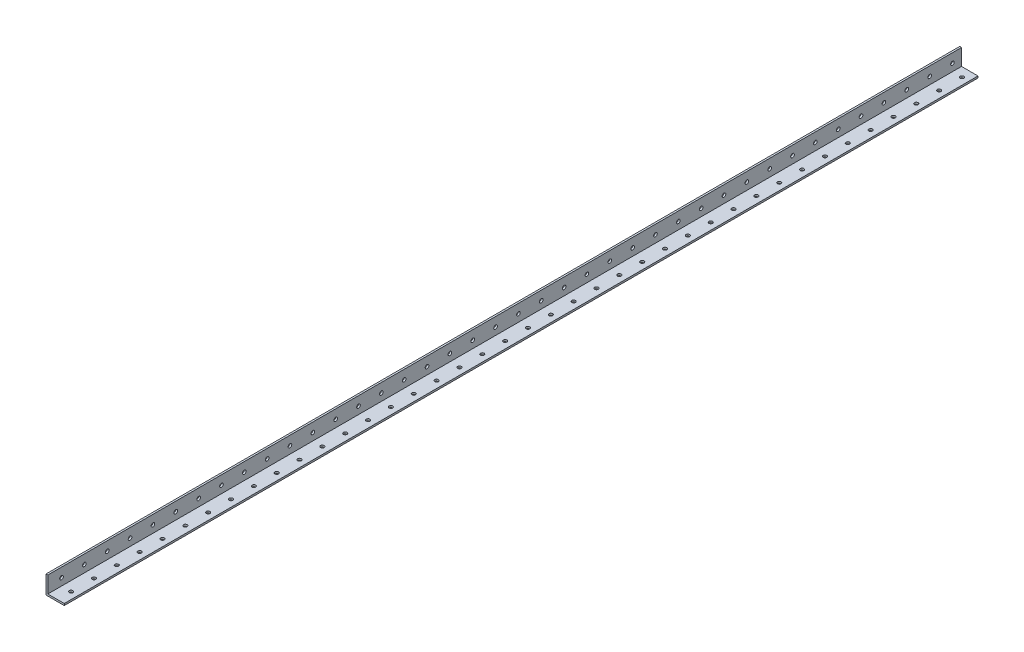
SolidWorks part; units mm, degrees
material "Aleación 6061"
ref_plane "Plan de face" through (0, 0, 0) normal (0, 0, 1) x (1, 0, 0)
ref_plane "Plan de dessus" through (0, 0, 0) normal (0, 1, 0) x (1, 0, 0)
ref_plane "Plan de droite" through (0, 0, 0) normal (1, 0, 0) x (0, 0, -1)
sketch "Croquis1" plane through (0, 0, 0) normal (0, 0, 1) x (1, 0, 0)
  line L0 (0, 0) -> (0, 40)
  line L1 (0, 40) -> (4, 40)
  line L2 (0, 0) -> (40, 0)
  line L3 (40, 0) -> (40, 4)
  line L4 (40, 4) -> (4, 4)
  line L5 (4, 4) -> (4, 40)
  dimension "D1" = 40
  dimension "D2" = 4
  dimension "D3" = 40
  dimension "D4" = 4
extrude "Saliente-Extruir1" add sketch "Croquis1" along normal blind 2000
sketch "Croquis2" plane through (0, 4, 0) normal (0, 1, 0) x (1, 0, 0)
  line L0 (40, -2000) -> (40, 0) construction
  line L1 (40, 0) -> (4, 0) construction
  circle A0 centre (25, -20) radius 4
  dimension "D1" = 8
  dimension "D2" = 15
  dimension "D3" = 20
extrude "Cortar-Extruir1" cut sketch "Croquis2" against normal blind 10
pattern_linear "MatrizL1" count 40 spacing 50 along (0, 0, 1) of "Cortar-Extruir1"
sketch "Sketch1" plane through (0, 0, 0) normal (-1, 0, 0) x (0, 0, 1)
  line L0 (2000, 40) -> (0, 40) construction
  line L2 (0, 40) -> (0, 0) construction
  circle A0 centre (20, 20) radius 4
  circle A1 centre (70, 20) radius 4
  circle A2 centre (120, 20) radius 4
  circle A3 centre (170, 20) radius 4
  circle A4 centre (220, 20) radius 4
  circle A5 centre (270, 20) radius 4
  circle A6 centre (320, 20) radius 4
  circle A7 centre (370, 20) radius 4
  circle A8 centre (420, 20) radius 4
  circle A9 centre (470, 20) radius 4
  circle A10 centre (520, 20) radius 4
  circle A11 centre (570, 20) radius 4
  circle A12 centre (620, 20) radius 4
  circle A13 centre (670, 20) radius 4
  circle A14 centre (720, 20) radius 4
  circle A15 centre (770, 20) radius 4
  circle A16 centre (820, 20) radius 4
  circle A17 centre (870, 20) radius 4
  circle A18 centre (920, 20) radius 4
  circle A19 centre (970, 20) radius 4
  circle A20 centre (1020, 20) radius 4
  circle A21 centre (1070, 20) radius 4
  circle A22 centre (1120, 20) radius 4
  circle A23 centre (1170, 20) radius 4
  circle A24 centre (1220, 20) radius 4
  circle A25 centre (1270, 20) radius 4
  circle A26 centre (1320, 20) radius 4
  circle A27 centre (1370, 20) radius 4
  circle A28 centre (1420, 20) radius 4
  circle A29 centre (1470, 20) radius 4
  circle A30 centre (1520, 20) radius 4
  circle A31 centre (1570, 20) radius 4
  circle A32 centre (1620, 20) radius 4
  circle A33 centre (1670, 20) radius 4
  circle A34 centre (1720, 20) radius 4
  circle A35 centre (1770, 20) radius 4
  circle A36 centre (1820, 20) radius 4
  circle A37 centre (1870, 20) radius 4
  circle A38 centre (1920, 20) radius 4
  circle A39 centre (1970, 20) radius 4
  dimension "D1" = 8
  dimension "D2" = 20
  dimension "D3" = 20
  dimension "D4" = 40
extrude "Cut-Extrude1" cut sketch "Sketch1" against normal blind 10
